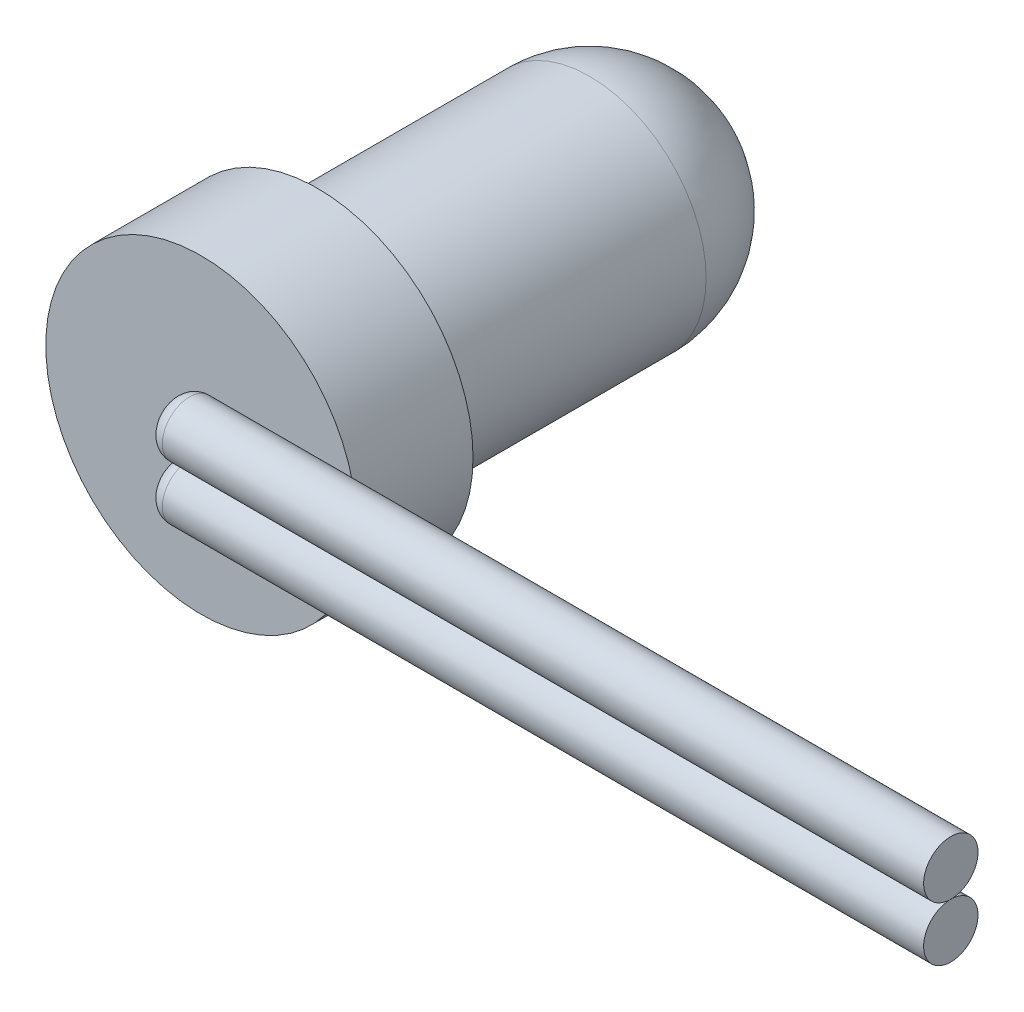
SolidWorks part; units mm, degrees
ref_plane "Front" through (0, 0, 0) normal (0, 0, 1) x (1, 0, 0)
ref_plane "Top" through (0, 0, 0) normal (0, 1, 0) x (1, 0, 0)
ref_plane "Right" through (0, 0, 0) normal (1, 0, 0) x (0, 0, -1)
sketch "Sketch1" plane through (0, 0, 0) normal (0, 0, 1) x (1, 0, 0)
  circle A0 centre (0, 0) radius 1.5
  dimension "D1" = 3
extrude "Extrude1" add sketch "Sketch1" along normal blind 5
sketch "Sketch2" plane through (0, 0, 5) normal (0, 0, 1) x (1, 0, 0)
  circle A0 centre (0, 0) radius 2
  dimension "D1" = 4
extrude "Extrude2" add sketch "Sketch2" along normal blind 1.5
fillet "Fillet1" radius 1.5 1 edges at (1.5, 0, 0)
sketch "Sketch3" plane through (0, 0, 0) normal (1, 0, 0) x (0, 0, -1)
  line L0 (-6.5, 2) -> (-6.5, -2) construction
  circle A0 centre (-6.85, 0.35) radius 0.35
  circle A1 centre (-6.85, -0.35) radius 0.35
  point P6 (-6.5, 0)
  dimension "D2" = 0.7
  dimension "D3" = 0.7
  dimension "D1" = 0.35
  dimension "D4" = 0.35
  dimension "D5" = 0.35
  dimension "D6" = 0.35
extrude "Extrude3" add sketch "Sketch3" along normal blind 10 contours A1 | A0
fillet "Fillet2" radius 0.2 1 edges at (0, -0.35, 6.5)
fillet "Fillet3" radius 0.2 1 edges at (0, 0.35, 6.5)
